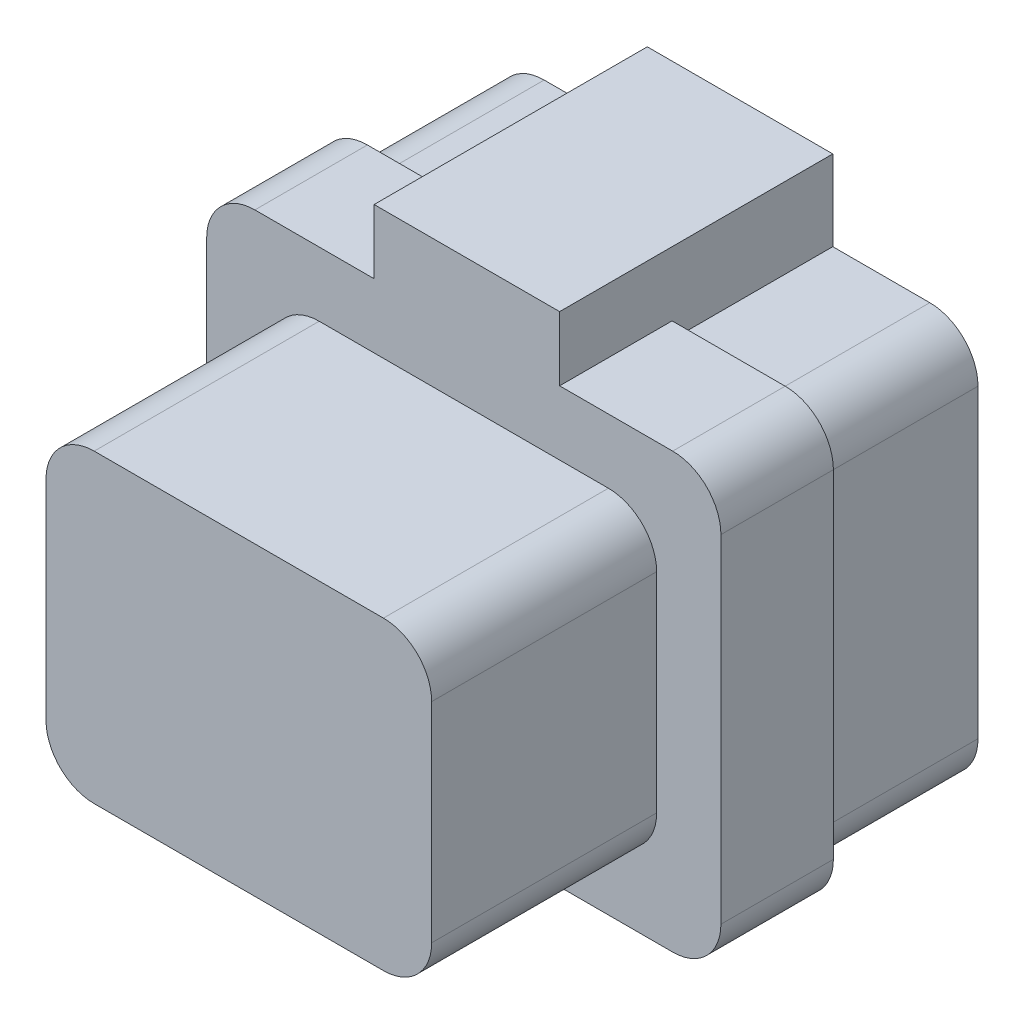
SolidWorks part; units mm, degrees
ref_plane "正面" through (0, 0, 0) normal (0, 0, 1) x (1, 0, 0)
ref_plane "平面" through (0, 0, 0) normal (0, 1, 0) x (1, 0, 0)
ref_plane "右側面" through (0, 0, 0) normal (1, 0, 0) x (0, 0, -1)
sketch "ｽｹｯﾁ1" plane through (0, 0, 0) normal (0, 0, 1) x (1, 0, 0)
  line L1 (0, 0) -> (32, 0)
  line L2 (0, 0) -> (0, 27)
  line L3 (0, 27) -> (32, 27)
  line L4 (32, 0) -> (32, 27)
  dimension "D1" = 32
  dimension "D2" = 27
extrude "ﾎﾞｽ - 押し出し1" add sketch "ｽｹｯﾁ1" along normal blind 7
sketch "ｽｹｯﾁ2" plane through (0, 0, 7) normal (0, 0, 1) x (1, 0, 0)
  line L8 (4, 23) -> (4, 4)
  line L9 (4, 4) -> (28, 4)
  line L10 (28, 4) -> (28, 23)
  line L11 (28, 23) -> (4, 23)
  line L12 (4, 23) -> (4, 4)
  line L13 (4, 4) -> (28, 4)
  line L14 (28, 4) -> (28, 23)
  line L15 (28, 23) -> (4, 23)
  dimension "D1" = 4
extrude "ﾎﾞｽ - 押し出し2" add sketch "ｽｹｯﾁ2" along normal blind 14
sketch "ｽｹｯﾁ3" plane through (0, 0, 0) normal (0, 0, -1) x (-1, 0, 0)
  line L8 (-1, 1) -> (-1, 26)
  line L9 (-1, 26) -> (-31, 26)
  line L10 (-31, 26) -> (-31, 1)
  line L11 (-31, 1) -> (-1, 1)
  line L12 (-1, 1) -> (-1, 26)
  line L13 (-1, 26) -> (-31, 26)
  line L14 (-31, 26) -> (-31, 1)
  line L15 (-31, 1) -> (-1, 1)
  dimension "D1" = 1
extrude "ﾎﾞｽ - 押し出し3" add sketch "ｽｹｯﾁ3" along normal blind 10
fillet "ﾌｨﾚｯﾄ1" radius 3 12 edges at (28, 4, 14) (32, 0, 3.5) (31, 1, -5) (4, 4, 14) (0, 0, 3.5) (1, 1, -5) (4, 23, 14) (0, 27, 3.5) (1, 26, -5) (28, 23, 14) (32, 27, 3.5) (31, 26, -5)
sketch "ｽｹｯﾁ4" plane through (0, 26, 0) normal (0, 1, 0) x (1, 0, 0)
  line L0 (4, 10) -> (28, 10) construction
  line L1 (10.4188, 10) -> (21.9634, 10)
  line L2 (10.4188, 10) -> (10.4188, -7)
  line L3 (10.4188, -7) -> (21.9634, -7)
  line L4 (21.9634, 10) -> (21.9634, -7)
  line L5 (29, -7) -> (3, -7) construction
extrude "ﾎﾞｽ - 押し出し4" add sketch "ｽｹｯﾁ4" along normal blind 5
sketch "ｽｹｯﾁ5" plane through (0, 0, -10) normal (0, 0, -1) x (-1, 0, 0)
  line L0 (-16.1911, 31) -> (-16.1911, 0) construction
  line L1 (-21.9634, 31) -> (-10.4188, 31) construction
  line L2 (-3, 0) -> (-29, 0) construction
  line L4 (-28, 1) -> (-4, 1) construction
  circle A0 centre (-16.1911, 13) radius 0.4
  circle A1 centre (-14.1911, 13) radius 0.4
  circle A2 centre (-12.1911, 13) radius 0.4
  circle A3 centre (-10.1911, 13) radius 0.4
  circle A4 centre (-8.1911, 13) radius 0.4
  circle A5 centre (-6.1911, 13) radius 0.4
  circle A6 centre (-16.1911, 18) radius 0.4
  circle A7 centre (-14.1911, 18) radius 0.4
  circle A8 centre (-12.1911, 18) radius 0.4
  circle A9 centre (-10.1911, 18) radius 0.4
  circle A10 centre (-8.1911, 18) radius 0.4
  circle A11 centre (-6.1911, 18) radius 0.4
  circle A12 centre (-16.1911, 8) radius 0.4
  circle A13 centre (-14.1911, 8) radius 0.4
  circle A14 centre (-12.1911, 8) radius 0.4
  circle A15 centre (-10.1911, 8) radius 0.4
  circle A16 centre (-8.1911, 8) radius 0.4
  circle A17 centre (-6.1911, 8) radius 0.4
  circle A18 centre (-26.1911, 18) radius 0.4
  circle A19 centre (-24.1911, 18) radius 0.4
  circle A20 centre (-22.1911, 18) radius 0.4
  circle A21 centre (-20.1911, 18) radius 0.4
  circle A22 centre (-16.1911, 18) radius 0.4
  circle A23 centre (-16.1911, 13) radius 0.4
  circle A24 centre (-18.1911, 13) radius 0.4
  circle A25 centre (-20.1911, 13) radius 0.4
  circle A26 centre (-22.1911, 13) radius 0.4
  circle A27 centre (-24.1911, 13) radius 0.4
  circle A28 centre (-26.1911, 13) radius 0.4
  circle A29 centre (-26.1911, 8) radius 0.4
  circle A30 centre (-24.1911, 8) radius 0.4
  circle A31 centre (-22.1911, 8) radius 0.4
  circle A32 centre (-20.1911, 8) radius 0.4
  circle A33 centre (-18.1911, 8) radius 0.4
  circle A34 centre (-18.1911, 18) radius 0.4
  circle A35 centre (-16.1911, 8) radius 0.4
  dimension "D1" = 0.8
  dimension "D9" = 10
  dimension "D6" = 5
  dimension "D7" = 10
  dimension "D8" = 5
  dimension "D10" = 12
  dimension "D2" = 6
  dimension "D3" = 2
  dimension "D4" = 2
  dimension "D5" = 2
extrude "ｶｯﾄ - 押し出し1" cut sketch "ｽｹｯﾁ5" against normal blind 1 contours A28 | A27 | A26 | A25 | A24 | A0 | A1 | A18 | A19 | A20 | A21 | A34 | A6 | A7 | A8 | A9 | A10 | A11 | A5 | A4 | A3 | A2 | A29 | A30 | A31 | A32 | A33 | A12 | A13 | A14 | A15 | A16 | A17
